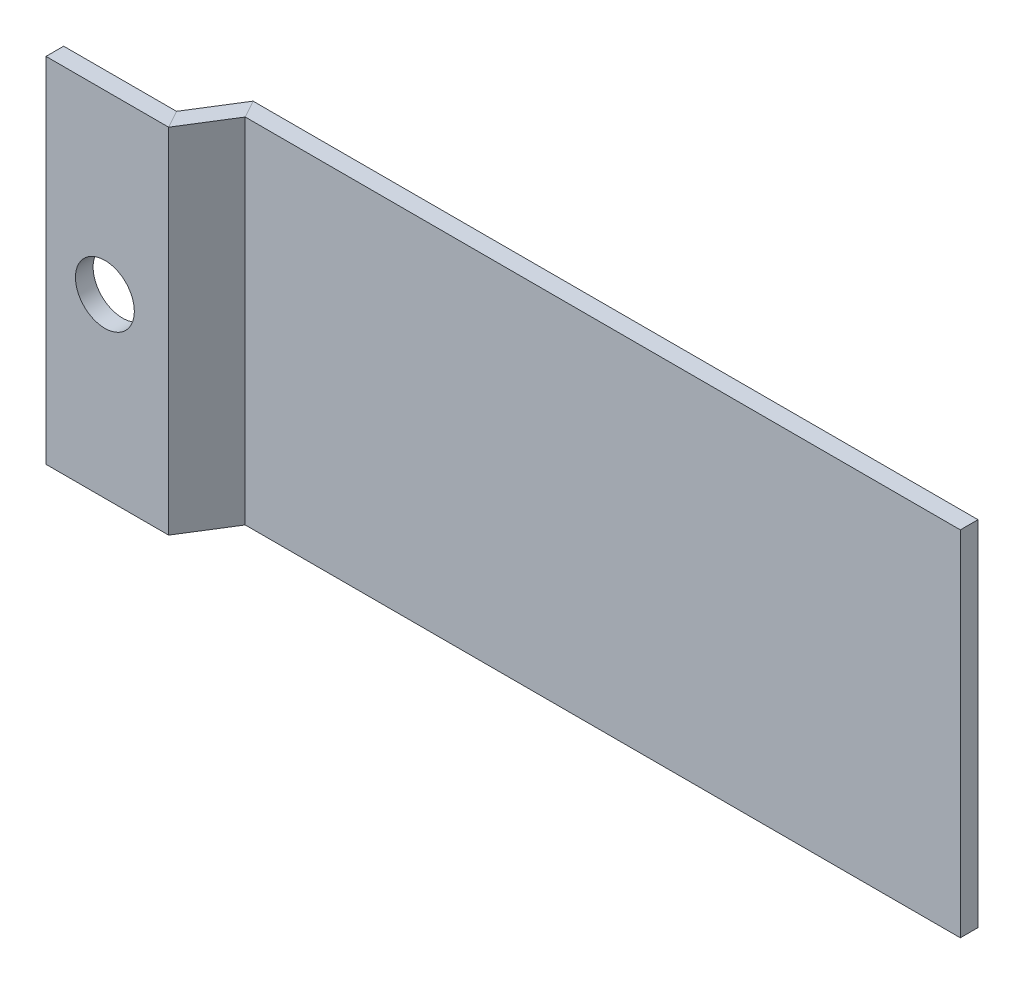
SolidWorks part; units mm, degrees
ref_plane "Front Plane" through (0, 0, 0) normal (0, 0, 1) x (1, 0, 0)
ref_plane "Top Plane" through (0, 0, 0) normal (0, 1, 0) x (1, 0, 0)
ref_plane "Right Plane" through (0, 0, 0) normal (1, 0, 0) x (0, 0, -1)
sketch "Sketch1" plane through (0, 0, 0) normal (0, 1, 0) x (1, 0, 0)
  line L0 (0, 0) -> (4, 0)
  line L1 (4, 0) -> (5, 1.6)
  line L2 (5, 1.6) -> (29.4547, 1.6)
  point P3 (11.9553, 1.3)
  point P6 (29.4547, 1.3)
  dimension "D1" = 1
  dimension "D2" = 4
  dimension "D3" = 1.6
sketch "Sketch2" plane through (0, 0, 0) normal (1, 0, 0) x (0, 0, -1)
  line L1 (-0.3, 6) -> (0.3, 6)
  line L2 (-0.3, 6) -> (-0.3, -6)
  line L3 (-0.3, -6) -> (0.3, -6)
  line L4 (0.3, 6) -> (0.3, -6)
  line L5 (-0.3, 6) -> (0.3, -6) construction
  line L6 (-0.3, -6) -> (0.3, 6) construction
  point P0 (0, 0)
  dimension "D1" = 0.6
  dimension "D2" = 12
sweep "Sweep1" add profiles "Sketch2" path "Sketch1"
sketch "Sketch3" plane through (0, 0, -0.3) normal (0, 0, -1) x (-1, 0, 0)
  line L0 (0, 0) -> (-4, 0) construction
  circle A0 centre (-2, 0) radius 1
  dimension "D1" = 2
  dimension "D2" = 2
extrude "Cut-Extrude1" cut sketch "Sketch3" against normal blind 10
